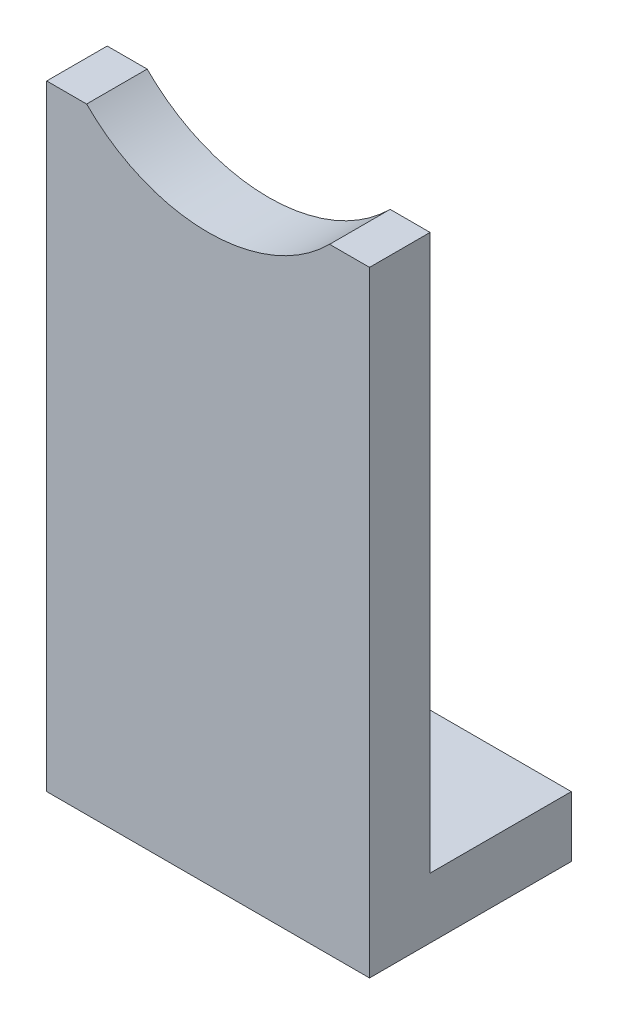
SolidWorks part; units mm, degrees
material "AISI 1010 钢，热轧条材"
ref_plane "前视基准面" through (0, 0, 0) normal (0, 0, 1) x (1, 0, 0)
ref_plane "上视基准面" through (0, 0, 0) normal (0, 1, 0) x (1, 0, 0)
ref_plane "右视基准面" through (0, 0, 0) normal (1, 0, 0) x (0, 0, -1)
sketch "草图1" plane through (0, 0, 0) normal (0, 1, 0) x (1, 0, 0)
  line L0 (0, 1.5607) -> (38.9364, 1.5607) construction
  line L1 (0, 0) -> (0, 57.9884) construction
  line L3 (-16, 21.5607) -> (16, 21.5607)
  line L4 (-16, 21.5607) -> (-16, 1.5607)
  line L5 (-16, 1.5607) -> (16, 1.5607)
  line L6 (16, 21.5607) -> (16, 1.5607)
  line L7 (-16, 21.5607) -> (16, 1.5607) construction
  line L8 (-16, 1.5607) -> (16, 21.5607) construction
  point P6 (0, 11.5607)
  dimension "D1" = 32
  dimension "D2" = 20
extrude "凸台-拉伸1" add sketch "草图1" along normal blind 6
sketch "草图2" plane through (0, 6, 0) normal (0, 1, 0) x (1, 0, 0)
  line L1 (16, 1.5607) -> (-16, 1.5607)
  line L2 (16, 1.5607) -> (16, 7.5607)
  line L3 (16, 7.5607) -> (-16, 7.5607)
  line L4 (-16, 1.5607) -> (-16, 7.5607)
  dimension "D1" = 6
extrude "凸台-拉伸2" add sketch "草图2" along normal blind 55
sketch "草图3" plane through (0, 0, -1.5607) normal (0, 0, 1) x (1, 0, 0)
  line L0 (0, 0) -> (0, 75.9639) construction
  line L1 (-16, 61) -> (16, 61) construction
  circle A0 centre (0, 73) radius 17
  dimension "D1" = 34
  dimension "D2" = 12
extrude "切除-拉伸1" cut sketch "草图3" against normal blind 55
